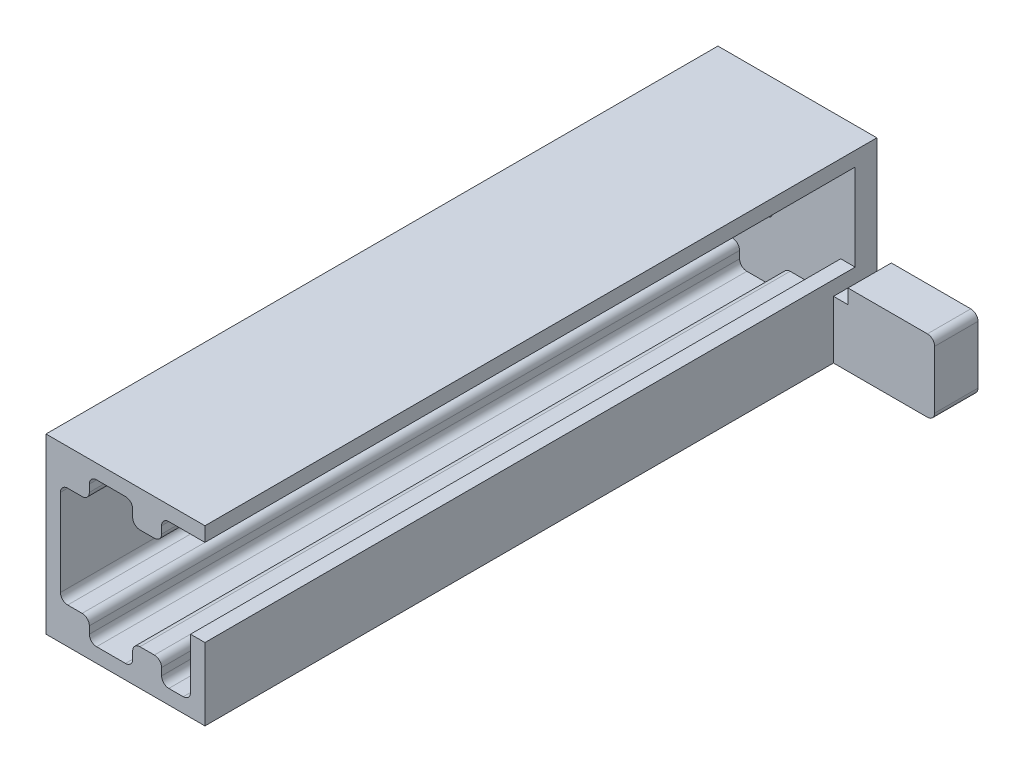
SolidWorks part; units mm, degrees
ref_plane "Front" through (0, 0, 0) normal (0, 0, 1) x (1, 0, 0)
ref_plane "Top" through (0, 0, 0) normal (0, 1, 0) x (1, 0, 0)
ref_plane "Right" through (0, 0, 0) normal (1, 0, 0) x (0, 0, -1)
sketch "Sketch1" plane through (0, 0, 0) normal (0, 0, 1) x (1, 0, 0)
  line L0 (27.94, 30.48) -> (27.94, 27.94)
  line L1 (0, 30.48) -> (27.94, 30.48)
  line L2 (0, 30.48) -> (0, 0)
  line L3 (0, 0) -> (27.94, 0)
  line L6 (2.54, 24.13) -> (2.54, 6.35)
  line L11 (27.94, 2.54) -> (27.94, 0)
  line L12 (2.54, 24.13) -> (7.62, 24.13)
  line L13 (7.62, 24.13) -> (7.62, 27.94)
  line L14 (7.62, 27.94) -> (15.24, 27.94)
  line L15 (15.24, 27.94) -> (15.24, 24.13)
  line L16 (15.24, 24.13) -> (20.32, 24.13)
  line L17 (20.32, 24.13) -> (20.32, 27.94)
  line L18 (20.32, 27.94) -> (27.94, 27.94)
  line L19 (2.54, 6.35) -> (7.62, 6.35)
  line L20 (7.62, 6.35) -> (7.62, 2.54)
  line L21 (7.62, 2.54) -> (15.24, 2.54)
  line L22 (15.24, 2.54) -> (15.24, 6.35)
  line L23 (15.24, 6.35) -> (20.32, 6.35)
  line L24 (20.32, 6.35) -> (20.32, 2.54)
  line L25 (20.32, 2.54) -> (27.94, 2.54)
  point P21 (12.2844, 9.6359)
  point P22 (39.6767, 30.48)
  dimension "D1" = 7.62
  dimension "D2" = 7.62
  dimension "D3" = 2.54
  dimension "D4" = 5.08
  dimension "D5" = 3.81
  dimension "D6" = 25.4
  dimension "D7" = 2.54
  dimension "D8" = 2.54
extrude "Boss-Extrude1" add sketch "Sketch1" along normal blind 114.3
ref_plane "Plane1" through (0, 15.24, 0) normal (0, 1, 0) x (1, 0, 0)
sketch "Sketch6" plane through (0, 0, 0) normal (0, 0, -1) x (-1, 0, 0)
  line L1 (-27.94, 30.48) -> (0, 30.48)
  line L2 (-27.94, 30.48) -> (-27.94, 0)
  line L3 (-27.94, 0) -> (0, 0)
  line L4 (0, 30.48) -> (0, 0)
extrude "Boss-Extrude5" add sketch "Sketch6" along normal blind 3.81
sketch "Sketch8" plane through (27.94, 0, 0) normal (1, 0, 0) x (0, 0, -1)
  line L1 (3.81, 0) -> (-3.81, 0)
  line L2 (3.81, 0) -> (3.81, 12.7)
  line L3 (3.81, 12.7) -> (-3.81, 12.7)
  line L4 (-3.81, 0) -> (-3.81, 12.7)
  dimension "D1" = 12.7
  dimension "D2" = 7.62
extrude "Boss-Extrude6" add sketch "Sketch8" along normal blind 17.78 contours L2 L1 L4 L3
sketch "Sketch9" plane through (0, 0, 0) normal (0, 0, 1) x (1, 0, 0)
  line L1 (27.94, 12.7) -> (25.4, 12.7)
  line L2 (27.94, 12.7) -> (27.94, 2.54)
  line L3 (27.94, 2.54) -> (25.4, 2.54)
  line L4 (25.4, 12.7) -> (25.4, 2.54)
  line L5 (27.94, 2.54) -> (20.32, 2.54) construction
  point P5 (0, 0)
  dimension "D1" = 2.54
extrude "Boss-Extrude7" add sketch "Sketch9" along normal through all
sketch "Sketch10" plane through (0, 0, 3.81) normal (0, 0, 1) x (1, 0, 0)
  line L1 (27.94, 12.7) -> (30.48, 12.7)
  line L2 (27.94, 12.7) -> (27.94, 10.16)
  line L3 (27.94, 10.16) -> (30.48, 10.16)
  line L4 (30.48, 12.7) -> (30.48, 10.16)
  dimension "D1" = 2.54
  dimension "D2" = 2.54
extrude "Cut-Extrude2" cut sketch "Sketch10" against normal through all
sketch "Sketch11" plane through (0, 0, 0) normal (0, 0, 1) x (1, 0, 0)
  line L0 (11.43, 27.94) -> (11.43, 2.54) construction
  line L1 (7.62, 27.94) -> (15.24, 27.94) construction
  line L2 (15.24, 2.54) -> (7.62, 2.54) construction
  line L3 (10.16, 13.4191) -> (12.7, 13.4191) construction
  circle A0 centre (10.16, 13.4191) radius 0.635
  circle A1 centre (12.7, 13.4191) radius 0.635
  point P8 (11.43, 13.4191)
  point P10 (11.43, 13.4191)
  dimension "D1" = 1.27
  dimension "D2" = 2.54
extrude "Cut-Extrude3" cut sketch "Sketch11" against normal through all
fillet "Fillet3" radius 1.27 15 edges at (25.4, 2.54, 57.15) (20.32, 2.54, 57.15) (20.32, 6.35, 57.15) (15.24, 6.35, 57.15) (15.24, 2.54, 57.15) (7.62, 2.54, 57.15) (7.62, 6.35, 57.15) (20.32, 27.94, 57.15) (15.24, 24.13, 57.15) (20.32, 24.13, 57.15) (15.24, 27.94, 57.15) (2.54, 6.35, 57.15) (2.54, 24.13, 57.15) (7.62, 24.13, 57.15) (7.62, 27.94, 57.15)
fillet "Fillet4" radius 1.27 2 edges at (45.72, 0, 0) (45.72, 12.7, 0)
